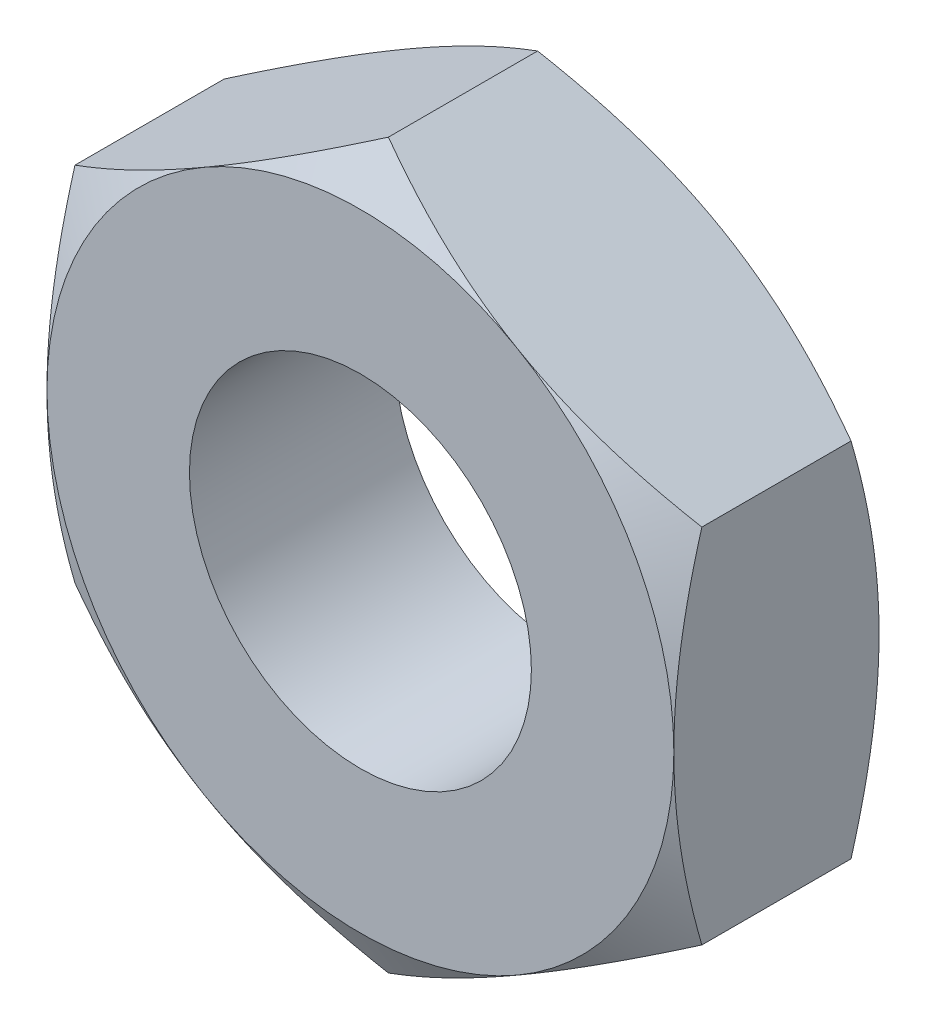
SolidWorks part; units mm, degrees
material "1.4000 (X6Cr13)"
ref_plane "Płaszczyzna przednia" through (0, 0, 0) normal (0, 0, 1) x (1, 0, 0)
ref_plane "Płaszczyzna górna" through (0, 0, 0) normal (0, 1, 0) x (1, 0, 0)
ref_plane "Płaszczyzna prawa" through (0, 0, 0) normal (1, 0, 0) x (0, 0, -1)
sketch "Szkic1" plane through (0, 0, 0) normal (0, 0, 1) x (1, 0, 0)
  line L1 (-2.75, 1.5877) -> (-2.75, -1.5877)
  line L2 (-2.75, -1.5877) -> (0, -3.1754)
  line L3 (0, -3.1754) -> (2.75, -1.5877)
  line L4 (2.75, -1.5877) -> (2.75, 1.5877)
  line L5 (2.75, 1.5877) -> (0, 3.1754)
  line L6 (0, 3.1754) -> (-2.75, 1.5877)
  circle A0 centre (0, 0) radius 1.5
  circle A1 centre (0, 0) radius 2.75 construction
  dimension "d" = 3
  dimension "s" = 5.5
extrude "Dodanie-wyciągnięcie1" add sketch "Szkic1" along normal mid plane 1.8
sketch "Szkic2" plane through (0, 0, 0.9) normal (0, 0, 1) x (1, 0, 0)
  circle A0 centre (0, 0) radius 2.75
  dimension "D1" = 5.5
extrude "Wytnij-wyciągnięcie2" cut sketch "Szkic2" against normal blind 1.8 draft 60 flip side to cut
mirror "Lustro1" about plane through (0, 0, 0) normal (0, 0, 1) of "Wytnij-wyciągnięcie2"
equation "\"D1@Szkic2\" = \"s@Szkic1\""
equation "\"D1@Wytnij-wyciągnięcie2\" = \"m@Dodanie-wyciągnięcie1\""
